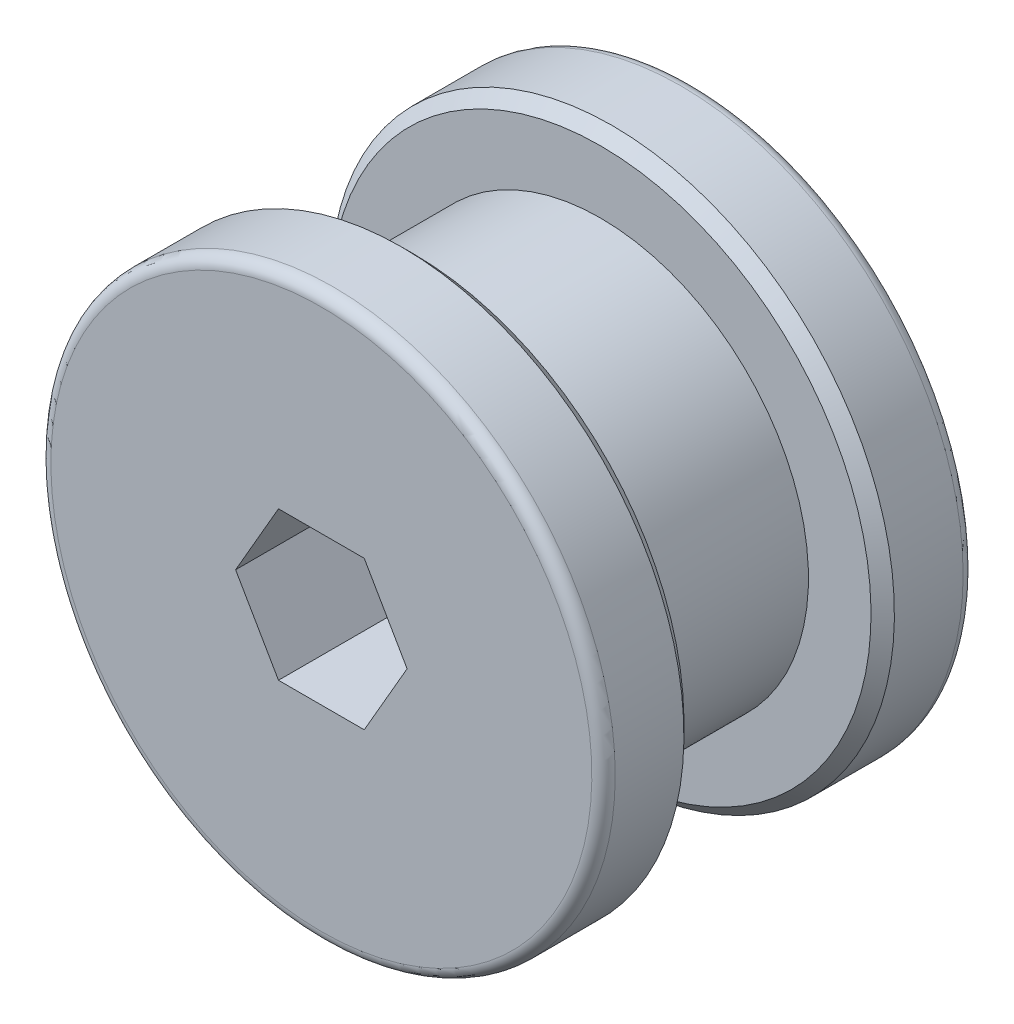
SolidWorks part; units mm, degrees
ref_plane "Front Plane" through (0, 0, 0) normal (0, 0, 1) x (1, 0, 0)
ref_plane "Top Plane" through (0, 0, 0) normal (0, 1, 0) x (1, 0, 0)
ref_plane "Right Plane" through (0, 0, 0) normal (1, 0, 0) x (0, 0, -1)
sketch "Sketch1" plane through (0, 0, 0) normal (1, 0, 0) x (0, 0, -1)
  line L0 (0, 26.7891) -> (0, -21.7289) construction
  line L1 (8, 17.78) -> (-8, 17.78)
  line L2 (-8, 17.78) -> (-8, 24.13)
  line L3 (-8, 24.13) -> (-15.875, 24.13)
  line L4 (15.875, 0) -> (-15.875, 0)
  line L5 (-15.875, 24.13) -> (-15.875, 0)
  line L6 (15.875, 24.13) -> (15.875, 0)
  line L7 (8, 17.78) -> (8, 24.13)
  line L9 (0, 17.78) -> (-8, 17.78)
  line L10 (-8, 17.78) -> (-8, 24.13)
  line L11 (-8, 24.13) -> (-15.875, 24.13)
  line L12 (8, 24.13) -> (15.875, 24.13)
  dimension "D1" = 16
  dimension "D2" = 24.13
  dimension "D3" = 31.75
  dimension "D4" = 6.35
revolve "Revolve3" add sketch "Sketch1" angle 360 about L4
fillet "Fillet1" radius 1 2 edges at (0, 24.13, -15.875) (0, 24.13, 15.875)
chamfer "Chamfer1" distance 1 angle 45 2 edges at (0, 24.13, 8) (0, 24.13, -8)
sketch "Sketch2" plane through (0, 0, 15.875) normal (0, 0, 1) x (1, 0, 0)
  line L1 (7.3323, 0) -> (3.6662, 6.35)
  line L2 (3.6662, 6.35) -> (-3.6662, 6.35)
  line L3 (-3.6662, 6.35) -> (-7.3323, 0)
  line L4 (-7.3323, 0) -> (-3.6662, -6.35)
  line L5 (-3.6662, -6.35) -> (3.6662, -6.35)
  line L6 (3.6662, -6.35) -> (7.3323, 0)
  circle A0 centre (0, 0) radius 6.35 construction
  point P1 (0, 0)
  dimension "D1" = 12.7
extrude "Cut-Extrude1" cut sketch "Sketch2" against normal through all both and the other way through all
